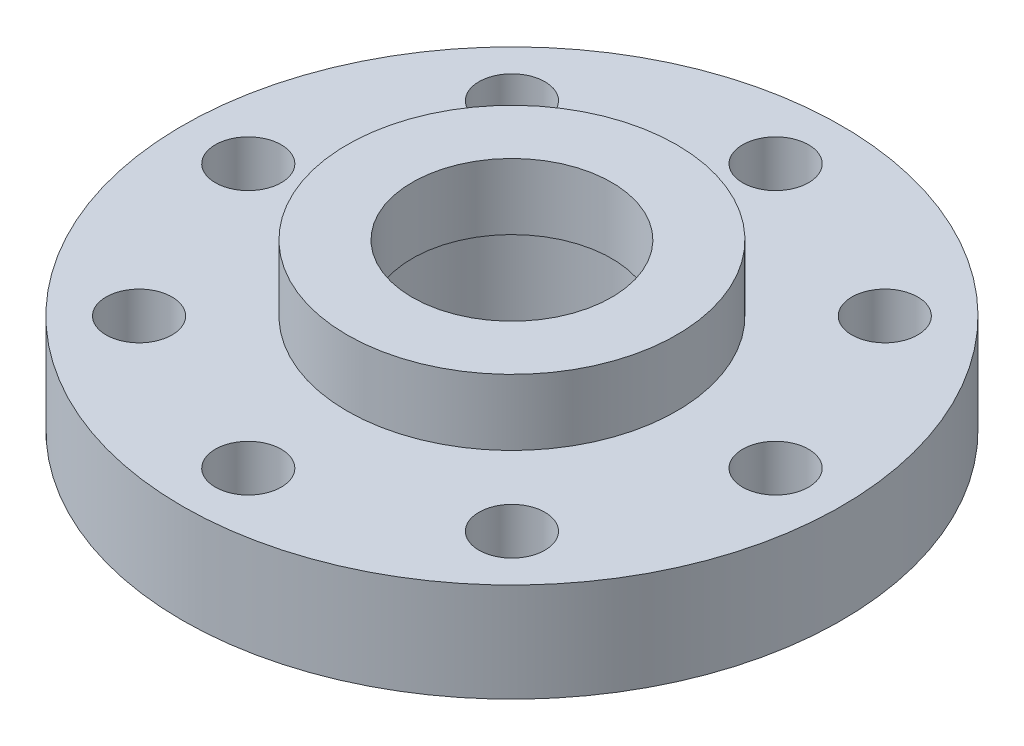
SolidWorks part; units mm, degrees
ref_plane "前视基准面" through (0, 0, 0) normal (0, 0, 1) x (1, 0, 0)
ref_plane "上视基准面" through (0, 0, 0) normal (0, 1, 0) x (1, 0, 0)
ref_plane "右视基准面" through (0, 0, 0) normal (1, 0, 0) x (0, 0, -1)
other "Configuration Table"
sketch "草图1" plane through (0, 0, 0) normal (0, 1, 0) x (1, 0, 0)
  circle A0 centre (0, 0) radius 10
  circle A1 centre (0, 0) radius 3.26
  circle A2 centre (0, 8) radius 1
  circle A3 centre (5.6569, 5.6569) radius 1
  circle A4 centre (8, 0) radius 1
  circle A5 centre (5.6569, -5.6569) radius 1
  circle A6 centre (0, -8) radius 1
  circle A7 centre (-5.6569, -5.6569) radius 1
  circle A8 centre (-8, 0) radius 1
  circle A9 centre (-5.6569, 5.6569) radius 1
  point P23 (0, 0)
  dimension "D1" = 20
  dimension "D2" = 6.52
  dimension "D3" = 2
  dimension "D4" = 8
  dimension "D5" = 8
extrude "凸台-拉伸1" add sketch "草图1" along normal blind 3
sketch "草图2" plane through (0, 3, 0) normal (0, 1, 0) x (1, 0, 0)
  circle A0 centre (0, 0) radius 5
  circle A3 centre (0, 0) radius 3.025
  dimension "D1" = 10
  dimension "D2" = 6.05
extrude "凸台-拉伸2" add sketch "草图2" along normal blind 2
